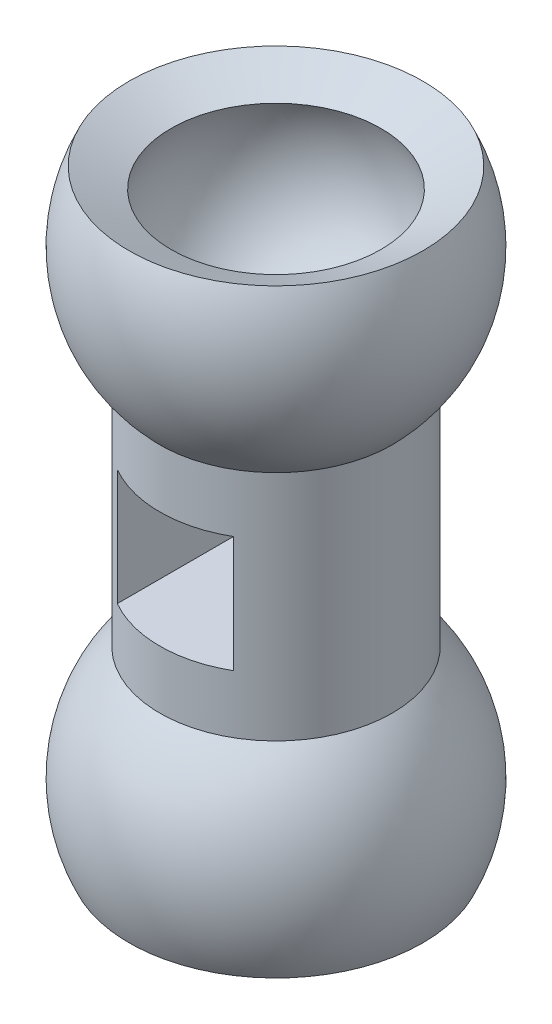
SolidWorks part; units mm, degrees
ref_plane "Front" through (0, 0, 0) normal (0, 0, 1) x (1, 0, 0)
ref_plane "Top" through (0, 0, 0) normal (0, 1, 0) x (1, 0, 0)
ref_plane "Right" through (0, 0, 0) normal (1, 0, 0) x (0, 0, -1)
sketch "Sketch1" plane through (0, 0, 0) normal (0, 0, 1) x (1, 0, 0)
  line L0 (5, -4.899) -> (5, -9.899)
  line L3 (4.5175, 2.1429) -> (6.3246, 3)
  line L4 (0, 12.863) -> (0, -43.0612) construction
  line L5 (5, -9.899) -> (0, -9.899)
  line L6 (3, -4) -> (3, -9.899) construction
  line L7 (0, -9.899) -> (0, -5)
  arc A0 (6.3246, 3) -> (5, -4.899) centre (0, 0) cw
  arc A1 (4.5175, 2.1429) -> (0, -5) centre (0, 0) cw
  arc A2 (4.5175, 2.1429) -> (3, -4) centre (0, 0) cw construction
  dimension "D4" = 5
  dimension "D2" = 5
  dimension "D3" = 3
  dimension "D5" = 5
  dimension "D1" = 2
revolve "Revolve1" add sketch "Sketch1" angle 360 about L4
sketch "Sketch3" plane through (0, 0, 0) normal (0, 0, 1) x (1, 0, 0)
  line L0 (-5, -9.899) -> (5, -9.899) construction
  line L1 (-2.5, -7.399) -> (2.5, -7.399)
  line L2 (-2.5, -7.399) -> (-2.5, -9.899)
  line L3 (-2.5, -9.899) -> (2.5, -9.899)
  line L4 (2.5, -7.399) -> (2.5, -9.899)
  line L5 (-2.5, -7.399) -> (2.5, -9.899) construction
  line L6 (-2.5, -9.899) -> (2.5, -7.399) construction
  point P0 (0, -8.649)
  dimension "D1" = 2.5
  dimension "D2" = 5
extrude "Cut-Extrude1" cut sketch "Sketch3" against normal through all both and the other way through all
mirror "Mirror1" about plane through (5, -9.899, 0) normal (0, 1, 0) of "Revolve1", "Cut-Extrude1"
